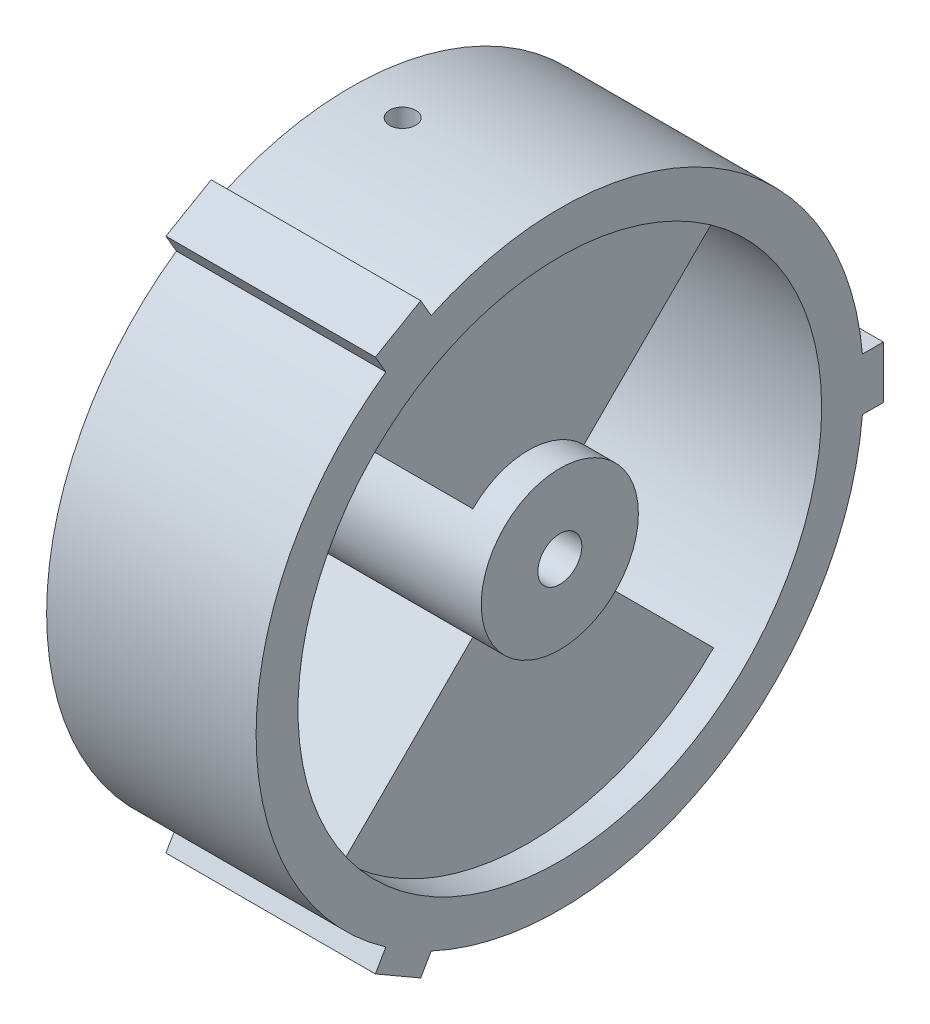
SolidWorks part; units mm, degrees
ref_plane "Alzado" through (0, 0, 0) normal (0, 0, 1) x (1, 0, 0)
ref_plane "Planta" through (0, 0, 0) normal (0, 1, 0) x (1, 0, 0)
ref_plane "Vista lateral" through (0, 0, 0) normal (1, 0, 0) x (0, 0, -1)
sketch "Croquis1" plane through (0, 0, 0) normal (0, 0, 1) x (1, 0, 0)
  line L0 (0, 0) -> (0, 2.1)
  line L1 (0, 2.1) -> (10, 2.1)
  line L2 (10, 2.1) -> (10, 29)
  line L3 (10, 29) -> (-10, 29)
  line L4 (-10, 29) -> (-10, 2.1)
  line L5 (-10, 2.1) -> (0, 2.1)
  line L6 (0, 0) -> (10, 0) construction
  dimension "D1" = 2.1
  dimension "D2" = 10
  dimension "D3" = 26.9
  dimension "D4" = 20
revolve "Revolución1" add sketch "Croquis1" angle 360 about L6
sketch "Croquis2" plane through (10, 0, 0) normal (1, 0, 0) x (0, 0, -1)
  circle A0 centre (0, 0) radius 29 construction
  circle A1 centre (0, 0) radius 29
  circle A2 centre (0, 0) radius 25
  circle A3 centre (0, 0) radius 7.5
  circle A4 centre (0, 0) radius 4.2
  dimension "D1" = 50
  dimension "D2" = 15
extrude "Cortar-Extruir1" cut sketch "Croquis2" against normal blind 3 contours A2 A3
sketch "Croquis3" plane through (10, 0, 0) normal (1, 0, 0) x (0, 0, -1)
  line L0 (-7.5, 0) -> (0, 7.5) construction
  line L1 (0, 7.5) -> (-3.75, 3.75) construction
  line L2 (-3.75, 3.75) -> (1.4849, -1.4849) construction
  line L3 (1.4849, -1.4849) -> (1.4849, 1.4849) construction
  line L4 (1.4849, 1.4849) -> (-1.4849, 1.4849) construction
  line L5 (-1.4849, 1.4849) -> (-1.4849, -1.4849) construction
  line L6 (-1.4849, -1.4849) -> (1.4849, -1.4849) construction
  line L7 (1.4849, 1.4849) -> (5.3033, 5.3033) construction
  line L8 (-1.4849, -1.4849) -> (-5.3033, -5.3033) construction
  line L9 (1.4849, -1.4849) -> (5.3033, -5.3033) construction
  line L10 (-3.75, 3.75) -> (-5.3033, 5.3033) construction
  line L11 (-5.3033, 5.3033) -> (-17.6777, 17.6777)
  line L12 (5.3033, 5.3033) -> (17.6777, 17.6777)
  line L13 (-5.3033, -5.3033) -> (-17.6777, -17.6777)
  line L14 (5.3033, -5.3033) -> (17.6777, -17.6777)
  circle A0 centre (0, 0) radius 7.5 construction
  circle A1 centre (0, 0) radius 25 construction
  circle A2 centre (0, 0) radius 7.5
  circle A3 centre (0, 0) radius 25
  circle A4 centre (0, 0) radius 2.1 construction
extrude "Cortar-Extruir3" cut sketch "Croquis3" against normal blind 73 contours L11 A3 L13 L1 | L14 A3 L12 L1
ref_plane "Plano1" through (0, 30, 0) normal (0, 1, 0) x (1, 0, 0)
sketch "Croquis4" plane through (0, 30, 0) normal (0, 1, 0) x (1, 0, 0)
  line L0 (-10, 29) -> (-10, -29) construction
  line L1 (-10, 29) -> (-10, -29)
  line L2 (-10, 0) -> (-5, 0)
  circle A0 centre (-5, 0) radius 1.25
  dimension "D2" = 2.5
  dimension "D1" = 5
extrude "Cortar-Extruir4" cut sketch "Croquis4" against normal blind 20
sketch "Croquis5" plane through (0, 10, 0) normal (0, 1, 0) x (1, 0, 0)
  circle A0 centre (-5, 0) radius 1
  dimension "D1" = 2
extrude "Cortar-Extruir5" cut sketch "Croquis5" against normal blind 10
sketch "Croquis6" plane through (-10, 0, 0) normal (-1, 0, 0) x (0, 0, 1)
  circle A0 centre (0, 0) radius 7.5
  circle A1 centre (0, 0) radius 24
extrude "Cortar-Extruir6" cut sketch "Croquis6" against normal blind 1
sketch "Croquis7" plane through (10, 0, 0) normal (1, 0, 0) x (0, 0, -1)
  line L0 (29, 2.5) -> (29, -2.5)
  line L1 (28.892, 2.5) -> (30.892, 2.5)
  line L2 (28.892, -2.5) -> (30.892, -2.5)
  line L3 (30.892, 2.5) -> (30.892, -2.5)
  circle A1 centre (0, 0) radius 29
  circle A2 centre (0, 0) radius 29
  point P6 (29, 0)
  circle M6 centre (0, 0) radius 29
  dimension "D2" = 5
  dimension "D3" = 2
  dimension "D4" = 2
  dimension "D1" = 0
extrude "Saliente-Extruir1" add sketch "Croquis7" against normal blind 20 contours L2 L0 M6 | L3 L1 L0 L2 | L1 L0 M6
pattern_circular "MatrizC1" count 3 over 360 about axis through (0, 0, 0) along (1, 0, 0) of "Saliente-Extruir1"
